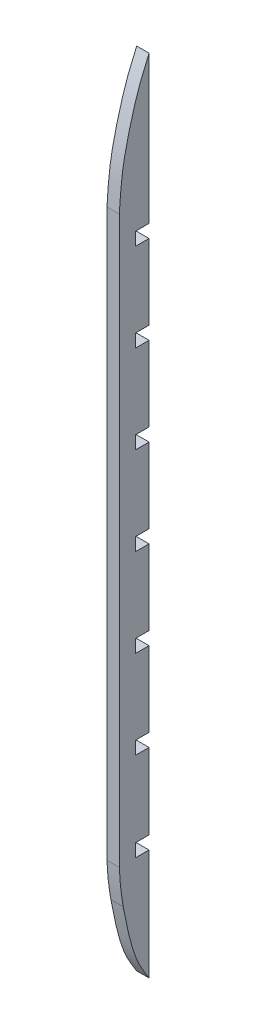
SolidWorks part; units mm, degrees
ref_plane "Alzado" through (0, 0, 0) normal (1, 0, 0) x (0, 1, 0)
ref_plane "Planta" through (0, 0, 0) normal (0, 0, 1) x (0, 1, 0)
ref_plane "Vista lateral" through (0, 0, 0) normal (0, 1, 0) x (-1, 0, 0)
sketch "Croquis1" plane through (0, 0, 0) normal (1, 0, 0) x (0, 1, 0)
  line L0 (-55.2341, -6.5787) -> (-38.6809, -6.5787)
  line L1 (60.4732, -6.5794) -> (60.4732, -3.6483)
  line L2 (60.4732, -3.6483) -> (57.6232, -3.6483)
  line L3 (57.6232, -3.6483) -> (57.6232, -6.5787)
  line L4 (57.6232, -6.5787) -> (41.2124, -6.5787)
  line L5 (41.2124, -6.5787) -> (41.2124, -3.6483)
  line L6 (41.2124, -3.6483) -> (38.3624, -3.6483)
  line L7 (38.3624, -3.6483) -> (38.3624, -6.5787)
  line L8 (38.3624, -6.5787) -> (21.9515, -6.5787)
  line L9 (21.9515, -6.5787) -> (21.9515, -3.6483)
  line L10 (21.9515, -3.6483) -> (19.1015, -3.6483)
  line L11 (19.1015, -3.6483) -> (19.1015, -6.5787)
  line L12 (19.1015, -6.5787) -> (2.6907, -6.5787)
  line L13 (2.6907, -6.5787) -> (2.6907, -3.6483)
  line L14 (2.6907, -3.6483) -> (-0.1593, -3.6483)
  line L15 (-0.1593, -3.6483) -> (-0.1593, -6.5787)
  line L16 (-0.1593, -6.5787) -> (-16.5701, -6.5787)
  line L17 (-16.5701, -6.5787) -> (-16.5701, -3.6483)
  line L18 (-16.5701, -3.6483) -> (-19.4201, -3.6483)
  line L19 (-19.4201, -3.6483) -> (-19.4201, -6.5787)
  line L20 (-19.4201, -6.5787) -> (-35.8309, -6.5787)
  line L21 (-35.8309, -6.5787) -> (-35.8309, -3.6483)
  line L22 (-35.8309, -3.6483) -> (-38.6809, -3.6483)
  line L23 (-38.6809, -3.6483) -> (-38.6809, -6.5787)
  line L24 (-55.2341, -6.5787) -> (-55.2341, -3.6483)
  line L25 (-55.2341, -3.6483) -> (-58.0841, -3.6483)
  line L26 (-58.0841, -3.6483) -> (-58.0841, -6.5787)
  line L27 (-58.0841, -6.5787) -> (-82.3082, -6.5787)
  line L28 (-58.1205, -0.0787) -> (-58.084, -0.0787)
  line L29 (92.6918, -6.5794) -> (60.4732, -6.5794)
  line L30 (-58.084, -0.0787) -> (65.5157, -0.0787)
  spline S0 degree 3 poles (-82.3082, -6.5787) (-82.2577, -6.5394) (-82.1843, -6.4822) (-82.1082, -6.4289) (-82.0845, -6.4123) knots 0 0 0 0 0.688452 1 1 1 1
  spline S1 degree 3 poles (-82.0845, -6.4123) (-80.7964, -5.6184) (-78.0963, -3.9545) (-72.6173, -2.2195) (-68.4999, -1.4228) (-66.0043, -0.9399) knots 0 0 0 0 0.264372 0.554139 1 1 1 1
  spline S2 degree 3 poles (-66.0043, -0.9399) (-64.3874, -0.6803) (-61.7728, -0.2603) (-59.1293, -0.1289) (-58.1205, -0.0787) knots 0 0 0 0 0.618397 1 1 1 1
  spline S3 degree 3 poles (65.5157, -0.0787) (68.1973, -0.259) (73.7724, -0.6337) (81.258, -2.4654) (87.6727, -4.3763) (91.1462, -5.901) (92.6918, -6.5794) knots 0 0 0 0 0.28639 0.595429 0.819983 1 1 1 1
  point P35 (0, 0)
  point P36 (0, 0)
  dimension "D1" = 2.85
  dimension "D2" = 2.85
  dimension "D3" = 2.85
  dimension "D4" = 2.85
  dimension "D5" = 2.85
  dimension "D6" = 2.85
  dimension "D7" = 2.85
  dimension "D8" = 6.5
  dimension "D9" = 6.5
  dimension "D10" = 6.5
  dimension "D11" = 6.5
  dimension "D12" = 6.5
  dimension "D13" = 6.5
  dimension "D14" = 6.5
  dimension "D15" = 175
extrude "Saliente-Extruir1" add sketch "Croquis1" along normal blind 2.7
